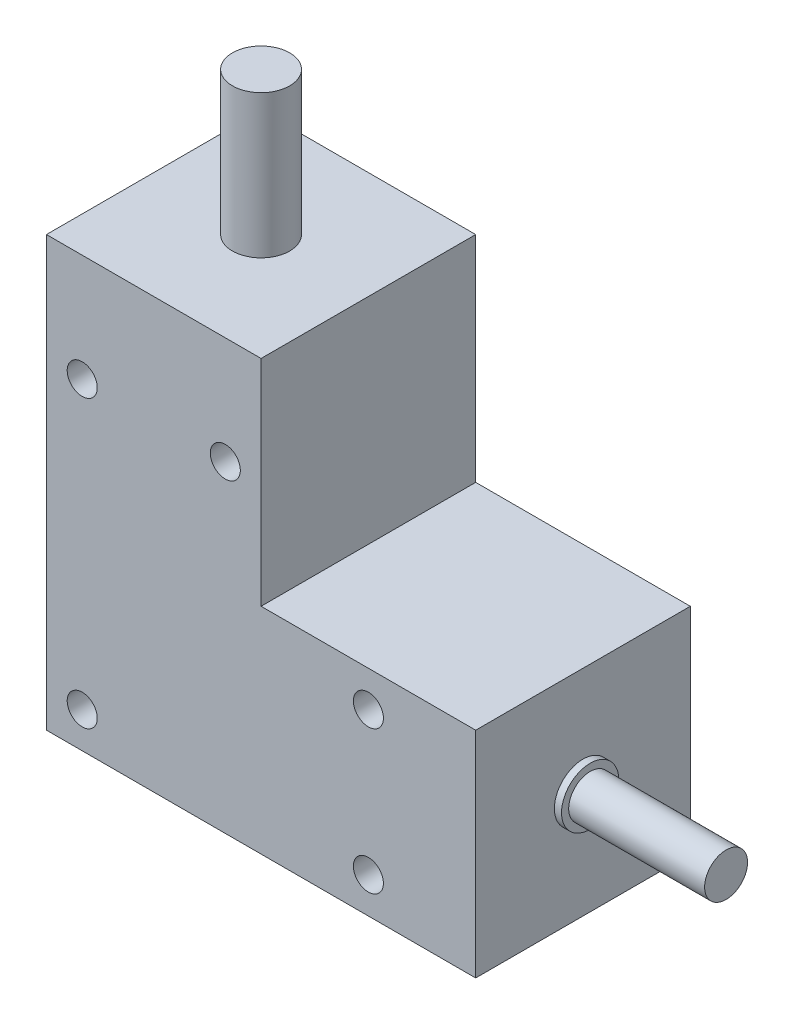
SolidWorks part; units mm, degrees
material "ABS"
ref_plane "Plan de face" through (0, 0, 0) normal (0, 0, 1) x (1, 0, 0)
ref_plane "Plan de dessus" through (0, 0, 0) normal (0, 1, 0) x (1, 0, 0)
ref_plane "Plan de droite" through (0, 0, 0) normal (1, 0, 0) x (0, 0, -1)
sketch "Esquisse1" plane through (0, 0, 0) normal (0, 0, 1) x (1, 0, 0)
  line L0 (0, 60) -> (30, 60)
  line L1 (30, 60) -> (30, 30)
  line L2 (30, 30) -> (60, 30)
  line L3 (60, 30) -> (60, 0)
  line L4 (60, 0) -> (0, 0)
  line L5 (0, 0) -> (0, 60)
  dimension "D1" = 60
  dimension "D2" = 60
  dimension "D3" = 30
  dimension "D4" = 30
extrude "Boss.-Extru.1" add sketch "Esquisse1" along normal mid plane 30
sketch "Esquisse3" plane through (0, 60, 0) normal (0, 1, 0) x (-1, 0, 0)
  line L0 (-30, 15) -> (0, 15) construction
  line L1 (0, 15) -> (0, -15) construction
  circle A0 centre (-15, 0) radius 4
  dimension "D3" = 8
  dimension "D1" = 15
  dimension "D2" = 15
extrude "Boss.-Extru.2" add sketch "Esquisse3" along normal blind 20
sketch "Esquisse4" plane through (60, 0, 0) normal (1, 0, 0) x (0, 0, -1)
  line L0 (-15, 0) -> (15, 0) construction
  line L1 (15, 0) -> (15, 30) construction
  circle A0 centre (0, 15) radius 4
  dimension "D3" = 8
  dimension "D1" = 15
  dimension "D2" = 15
extrude "Boss.-Extru.3" add sketch "Esquisse4" along normal blind 20
hole_wizard "Trou taraudé M5x0.82" positions "Esquisse3D1" profile "Esquisse8" tap size "M5x0.8" standard "Ansi Métrique"
sketch3d "Esquisse3D1"
  line L0 (60, 0, 15) -> (60, 30, 15) construction
  line L1 (0, 0, 15) -> (60, 0, 15) construction
  point P1 (45, 5, 15)
  dimension "D1" = 15
  dimension "D2" = 5
sketch "Esquisse8" plane through (45, 5, 15) normal (1, 0, 0) x (0, -1, 0)
  line L0 (0, 0) -> (0, 8.2618)
  line L1 (0, 8.2618) -> (2.1, 7)
  line L2 (2.1, 7) -> (2.1, 0)
  line L5 (2.1, 0) -> (0, 0)
  line L10 (0, 8.2618) -> (-2.1, 7) construction
  line L11 (0, -6.35) -> (0, 107.95) construction
  dimension "Diamètre du trou pour taraudage" = 4.2
  dimension "Profondeur du trou pour taraudage" = 7
  dimension "Angle de pointe" = 118
cosmetic thread "Filetage de perçage2" parameters "D1"=6.2, "D2"=5
hole_wizard "Trou taraudé M5x0.83" positions "Esquisse3D2" profile "Esquisse9" tap size "M5x0.8" standard "Ansi Métrique"
sketch3d "Esquisse3D2"
  line L1 (60, 30, 15) -> (30, 30, 15) construction
  line L2 (60, 0, 15) -> (60, 30, 15) construction
  point P2 (45, 25, 15)
  dimension "D1" = 5
  dimension "D2" = 15
sketch "Esquisse9" plane through (45, 25, 15) normal (1, 0, 0) x (0, -1, 0)
  line L0 (0, 0) -> (0, 8.2618)
  line L1 (0, 8.2618) -> (2.1, 7)
  line L2 (2.1, 7) -> (2.1, 0)
  line L5 (2.1, 0) -> (0, 0)
  line L10 (0, 8.2618) -> (-2.1, 7) construction
  line L11 (0, -6.35) -> (0, 107.95) construction
  dimension "Diamètre du trou pour taraudage" = 4.2
  dimension "Profondeur du trou pour taraudage" = 7
  dimension "Angle de pointe" = 118
cosmetic thread "Filetage de perçage3" parameters "D1"=6.2, "D2"=5
hole_wizard "Trou taraudé M5x0.84" positions "Esquisse11" profile "Esquisse10" tap size "M5x0.8" standard "Ansi Métrique"
sketch "Esquisse11" plane through (0, 0, 15) normal (0, 0, 1) x (1, 0, 0)
  line L0 (30, 60) -> (0, 60) construction
  line L1 (0, 60) -> (0, 0) construction
  point P0 (5, 45)
  dimension "D1" = 15
  dimension "D2" = 5
sketch "Esquisse10" plane through (5, 45, 15) normal (1, 0, 0) x (0, -1, 0)
  line L0 (0, 0) -> (0, 8.2618)
  line L1 (0, 8.2618) -> (2.1, 7)
  line L2 (2.1, 7) -> (2.1, 0)
  line L5 (2.1, 0) -> (0, 0)
  line L10 (0, 8.2618) -> (-2.1, 7) construction
  line L11 (0, -6.35) -> (0, 107.95) construction
  dimension "Diamètre du trou pour taraudage" = 4.2
  dimension "Profondeur du trou pour taraudage" = 7
  dimension "Angle de pointe" = 118
cosmetic thread "Filetage de perçage4" parameters "D1"=6.2, "D2"=5
hole_wizard "Trou taraudé M5x0.85" positions "Esquisse3D3" profile "Esquisse12" tap size "M5x0.8" standard "Ansi Métrique"
sketch3d "Esquisse3D3"
  line L0 (30, 30, 15) -> (30, 60, 15) construction
  line L1 (30, 60, 15) -> (0, 60, 15) construction
  line L2 (0, 0, 15) -> (60, 0, 15) construction
  line L3 (0, 60, 15) -> (0, 0, 15) construction
  point P0 (25, 45, 15)
  point P2 (5, 5, 15)
  dimension "D1" = 5
  dimension "D2" = 15
  dimension "D3" = 5
  dimension "D4" = 5
sketch "Esquisse12" plane through (25, 45, 15) normal (1, 0, 0) x (0, -1, 0)
  line L0 (0, 0) -> (0, 8.2618)
  line L1 (0, 8.2618) -> (2.1, 7)
  line L2 (2.1, 7) -> (2.1, 0)
  line L5 (2.1, 0) -> (0, 0)
  line L10 (0, 8.2618) -> (-2.1, 7) construction
  line L11 (0, -6.35) -> (0, 107.95) construction
  dimension "Diamètre du trou pour taraudage" = 4.2
  dimension "Profondeur du trou pour taraudage" = 7
  dimension "Angle de pointe" = 118
cosmetic thread "Filetage de perçage5" parameters "D1"=6.2, "D2"=5
cosmetic thread "Filetage de perçage6" parameters "D1"=6.2, "D2"=5
mirror "Symétrie1" about plane through (0, 0, 0) normal (0, 0, 1) of "Trou taraudé M5x0.85", "Trou taraudé M5x0.84", "Trou taraudé M5x0.83", "Trou taraudé M5x0.82"
sketch "Esquisse13" plane through (80, 0, 0) normal (1, 0, 0) x (0, 0, -1)
  circle A0 centre (0, 15) radius 4
  circle A1 centre (0, 15) radius 3
  circle A2 centre (0, 15) radius 4 construction
  dimension "D1" = 8
  dimension "D2" = 6
extrude "Enlèv. mat.-Extru.1" cut sketch "Esquisse13" against normal blind 19
